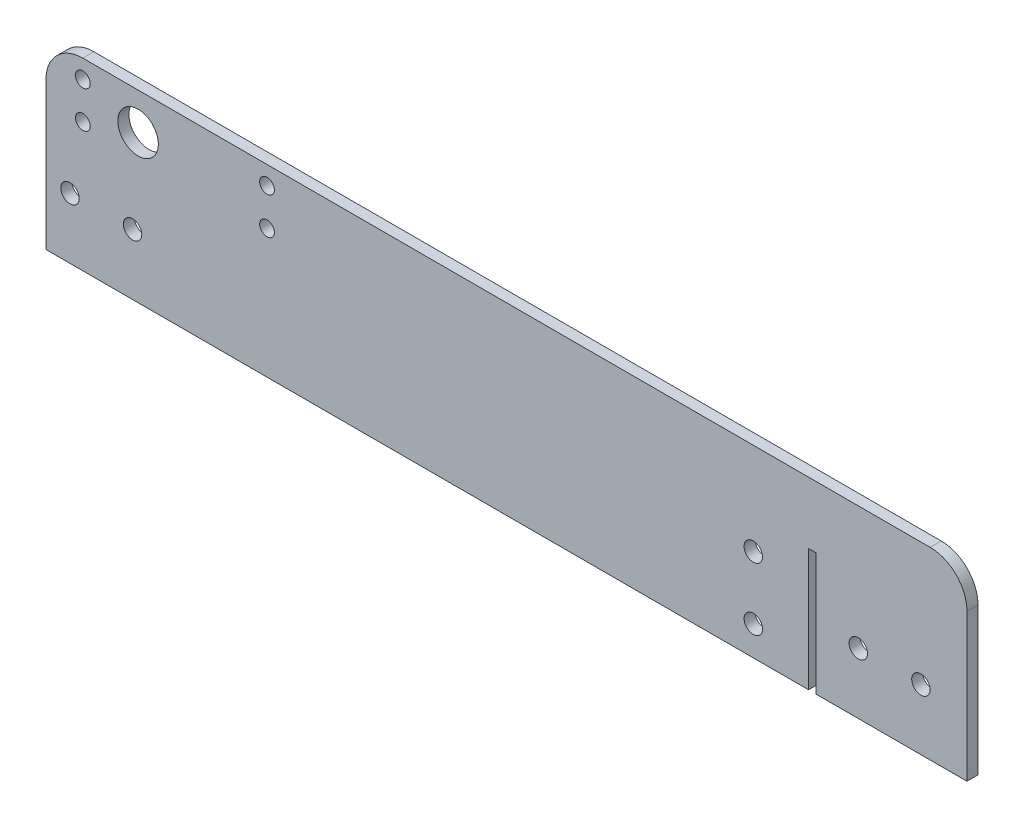
SolidWorks part; units mm, degrees
ref_plane "前视基准面" through (0, 0, 0) normal (0, 0, 1) x (1, 0, 0)
ref_plane "上视基准面" through (0, 0, 0) normal (0, 1, 0) x (1, 0, 0)
ref_plane "右视基准面" through (0, 0, 0) normal (1, 0, 0) x (0, 0, -1)
sketch "草图2" plane through (0, 0, 0) normal (0, 0, 1) x (1, 0, 0)
  line L0 (120, 0) -> (207, 0)
  line L1 (0, 0) -> (30, 0)
  line L2 (0, 0) -> (0, 40)
  line L3 (10, 50) -> (240, 50)
  line L4 (250, 0) -> (250, 40)
  line L9 (10, 45) -> (10, 35) construction
  line L10 (10, 40) -> (40, 40) construction
  line L11 (15, 0) -> (15, 21.8007) construction
  line L12 (30, 0) -> (120, 0)
  line L13 (207, 0) -> (207, 33.2159)
  line L14 (207, 33.2159) -> (208.9993, 33.2159)
  line L15 (208.9993, 33.2159) -> (208.9993, 0)
  line L16 (208.9993, 0) -> (250, 0)
  arc A2 (250, 40) -> (240, 50) centre (240, 40) ccw
  arc A3 (10, 50) -> (0, 40) centre (10, 40) ccw
  circle A4 centre (10, 45) radius 2
  circle A5 centre (10, 35) radius 2
  circle A6 centre (60, 45) radius 2
  circle A7 centre (60, 35) radius 2
  circle A8 centre (25, 40) radius 5.5
  circle A9 centre (6.5, 16.5) radius 2.5
  circle A10 centre (23.5, 16.5) radius 2.5
  circle A11 centre (220.5, 16.5) radius 2.5
  circle A12 centre (237.5, 16.5) radius 2.5
  point P11 (120, 15)
  point P18 (0, 50)
  dimension "D7" = 10
  dimension "D8" = 4
  dimension "D11" = 15
  dimension "D12" = 11
  dimension "D15" = 5
  dimension "D16" = 16.5
  dimension "D18" = 5
  dimension "D19" = 5
  dimension "D1" = 250
  dimension "D2" = 50
  dimension "D5" = 15
  dimension "D9" = 50
  dimension "D10" = 10
  dimension "D13" = 35
  dimension "D14" = 25
  dimension "D17" = 17
  dimension "D20" = 17
  dimension "D21" = 16.5
  dimension "D22" = 12.5
extrude "凸台-拉伸1" add sketch "草图2" along normal mid plane 3
sketch "草图3" plane through (0, 0, 1.5) normal (0, 0, 1) x (1, 0, 0)
  line L0 (0, 0) -> (207, 0) construction
  line L1 (250, 0) -> (250, 40) construction
  circle A0 centre (192, 25) radius 2.5
  circle A1 centre (192, 8) radius 2.5
  dimension "D1" = 5
  dimension "D2" = 5
  dimension "D3" = 17
  dimension "D4" = 8
  dimension "D5" = 58
extrude "切除-拉伸1" cut sketch "草图3" against normal blind 10
